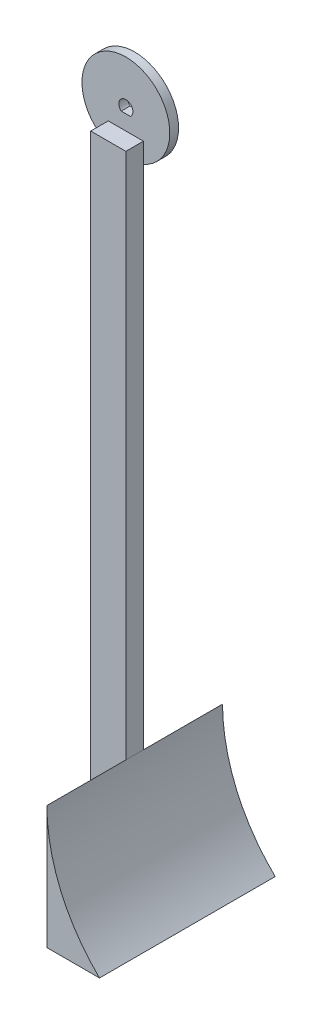
SolidWorks part; units mm, degrees
ref_plane "Front Plane" through (0, 0, 0) normal (0, 0, 1) x (1, 0, 0)
ref_plane "Top Plane" through (0, 0, 0) normal (0, 1, 0) x (1, 0, 0)
ref_plane "Right Plane" through (0, 0, 0) normal (1, 0, 0) x (0, 0, -1)
sketch "Sketch2" plane through (0, 0, 0) normal (0, 0, 1) x (1, 0, 0)
  line L0 (0, 2) -> (0, -1.5)
  line L1 (0, -13.75) -> (0, 13.75) construction
  line L2 (0, -1.5) -> (1.3229, -1.5)
  line L3 (0, -1.5) -> (-1.3229, -1.5)
  circle A0 centre (0, 0) radius 12.5
  arc A1 (1.3229, -1.5) -> (-1.3229, -1.5) centre (0, 0) ccw
  dimension "D1" = 4
extrude "Boss-Extrude1" add sketch "Sketch2" along normal blind 2.5 contours A0 A1 L2 L3
ref_plane "Plane1" through (0, 0, 2.5) normal (0, 0, 1) x (1, 0, 0)
sketch "Sketch4" plane through (0, 0, 2.5) normal (0, 0, 1) x (1, 0, 0)
  line L0 (-5, -165.7544) -> (5, -165.7544)
  line L1 (0, -13.75) -> (0, 13.75) construction
  line L2 (0, -5) -> (0, -5.7544)
  line L3 (0, -5.7544) -> (5, -5.7544)
  line L4 (0, -5.7544) -> (-5, -5.7544)
  line L5 (-5, -5.7544) -> (-5, -165.7544)
  line L6 (5, -165.7544) -> (5, -5.7544)
  line L7 (-5, -165.7544) -> (-5, -190.7544)
  line L8 (-5, -190.7544) -> (5, -190.7544)
extrude "Boss-Extrude2" add sketch "Sketch4" along normal blind 5 contours L0 L6 L3 L4 L5
ref_plane "Plane2" through (5, 0, 0) normal (1, 0, 0) x (0, 0, -1)
sketch "Sketch5" plane through (5, 0, 0) normal (1, 0, 0) x (0, 0, -1)
  line L0 (-5, -165.7544) -> (-5, -155.7544)
  line L1 (-7.5, -165.7544) -> (-2.5, -165.7544) construction
  line L2 (-5, -155.7544) -> (20, -155.7544)
  line L3 (-5, -155.7544) -> (-30, -155.7544)
  line L4 (20, -155.7544) -> (20, -190.7544)
  line L5 (-30, -155.7544) -> (-30, -190.7544)
  line L8 (-5, -190.7544) -> (-30, -190.7544)
  line L9 (-5, -190.7544) -> (20, -190.7544)
extrude "Boss-Extrude3" add sketch "Sketch5" along normal blind 15
ref_plane "Plane4" through (-5, 0, 0) normal (-1, 0, 0) x (0, 0, 1)
sketch "Sketch9" plane through (-5, 0, 0) normal (-1, 0, 0) x (0, 0, 1)
  line L0 (7.5, -165.7544) -> (7.5, -190.7544)
  line L1 (2.5, -165.7544) -> (7.5, -165.7544)
  line L2 (2.5, -165.7544) -> (2.5, -190.7544)
  line L3 (-20, -190.7544) -> (30, -190.7544) construction
  line L4 (2.5, -190.7544) -> (7.5, -190.7544)
extrude "Boss-Extrude4" add sketch "Sketch9" against normal blind 10
ref_plane "Plane3" through (0, 0, -20) normal (0, 0, -1) x (-1, 0, 0)
sketch "Sketch6" plane through (0, 0, -20) normal (0, 0, -1) x (-1, 0, 0)
  line L0 (-5, -155.7544) -> (-20, -155.7544)
  line L1 (-20, -155.7544) -> (-20, -190.7544)
  arc A0 (-5, -155.7544) -> (-20, -190.7544) centre (-54.0319, -155.455) cw
extrude "Cut-Extrude1" cut sketch "Sketch6" against normal blind 142
sketch "Sketch10" plane through (-5, 0, 0) normal (-1, 0, 0) x (0, 0, 1)
  line L0 (5, -190.7544) -> (5, -155.0559)
  line L1 (2.5, -190.7544) -> (7.5, -190.7544) construction
  line L2 (5, -155.0559) -> (2.5, -155.0559)
  line L3 (5, -190.7544) -> (5, -163.2544)
  line L4 (2.5, -11.4564) -> (2.5, -190.7544) construction
  line L5 (2.5, -155.0559) -> (7.7769, -155.0559)
